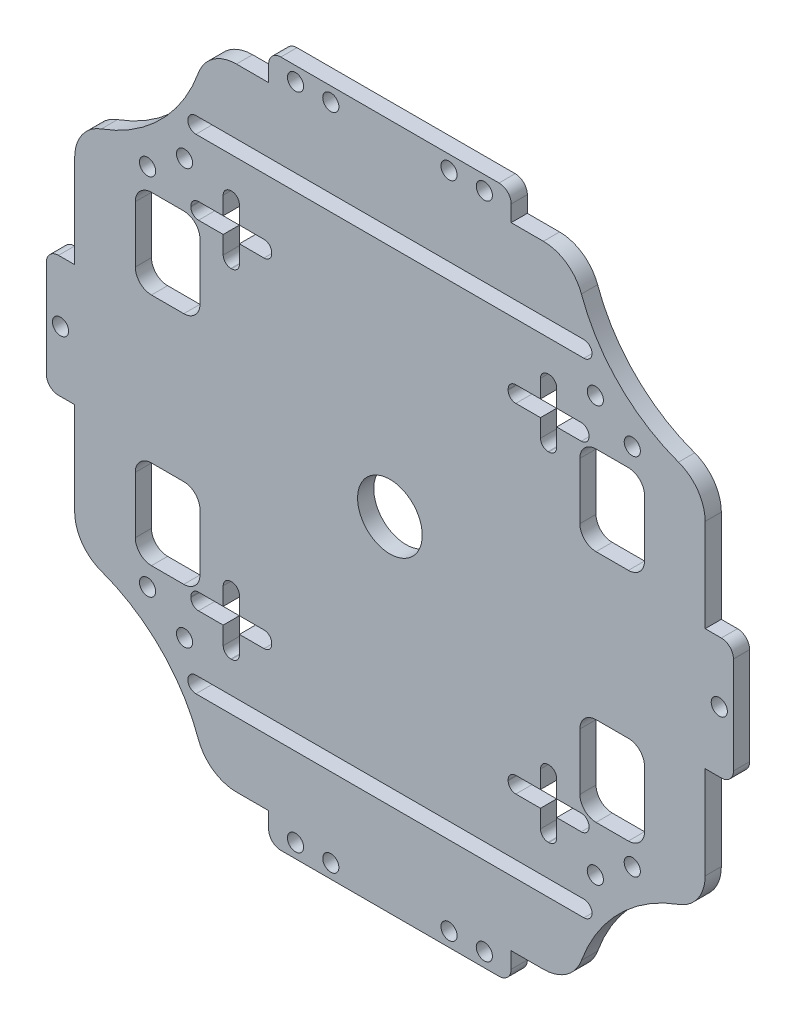
SolidWorks part; units mm, degrees
ref_plane "Front Plane" through (0, 0, 0) normal (0, 0, 1) x (1, 0, 0)
ref_plane "Top Plane" through (0, 0, 0) normal (0, 1, 0) x (1, 0, 0)
ref_plane "Right Plane" through (0, 0, 0) normal (1, 0, 0) x (0, 0, -1)
sketch "Sketch2" plane through (0, 0, 0) normal (0, 0, 1) x (1, 0, 0)
  line L0 (-37.25, 1.35) -> (-31.15, 1.35)
  line L2 (-85, -54.5) -> (-85, -30.5)
  line L4 (85, -54.5) -> (85, -30.5)
  line L7 (-27, 42.5) -> (27, 42.5)
  line L8 (30, 35.5) -> (30, 39.5)
  line L9 (30, 35.5) -> (37.9787, 35.5)
  line L10 (-30, 35.5) -> (-37.9787, 35.5)
  line L11 (-30, 35.5) -> (-30, 39.5)
  line L12 (82, -27.5) -> (78, -27.5)
  line L13 (-82, -57.5) -> (-78, -57.5)
  line L14 (78, -27.5) -> (78, -4.5213)
  line L15 (-78, -27.5) -> (-78, -4.5213)
  line L16 (-82, -27.5) -> (-78, -27.5)
  line L17 (-78, -57.5) -> (-78, -80.4787)
  line L18 (78, -57.5) -> (78, -80.4787)
  line L19 (82, -57.5) -> (78, -57.5)
  line L20 (-30, -120.5) -> (-30, -124.5)
  line L21 (-30, -120.5) -> (-37.9787, -120.5)
  line L22 (30, -120.5) -> (37.9787, -120.5)
  line L23 (30, -120.5) -> (30, -124.5)
  line L24 (-27, -127.5) -> (27, -127.5)
  line L27 (51, -2.5) -> (59, -2.5)
  line L30 (47, -6.5) -> (47, -20.5)
  line L31 (51, -24.5) -> (59, -24.5)
  line L32 (63, -6.5) -> (63, -20.5)
  line L34 (63, -78.5) -> (63, -64.5)
  line L35 (51, -82.5) -> (59, -82.5)
  line L36 (47, -78.5) -> (47, -64.5)
  line L37 (51, -60.5) -> (59, -60.5)
  line L38 (-51, -60.5) -> (-59, -60.5)
  line L39 (-47, -78.5) -> (-47, -64.5)
  line L40 (-51, -82.5) -> (-59, -82.5)
  line L41 (-63, -78.5) -> (-63, -64.5)
  line L42 (-63, -6.5) -> (-63, -20.5)
  line L43 (-51, -2.5) -> (-59, -2.5)
  line L44 (-47, -6.5) -> (-47, -20.5)
  line L45 (-51, -24.5) -> (-59, -24.5)
  line L46 (-48, -104.4522) -> (48, -104.4522)
  line L47 (-48, 19.4522) -> (48, 19.4522)
  line L49 (-48, 15.4522) -> (48, 15.4522)
  line L51 (-48, -100.4522) -> (48, -100.4522)
  line L71 (-47.35, -2.65) -> (-41.25, -2.65)
  line L72 (-49.25, -0.75) -> (-49.25, -0.55)
  line L73 (-47.35, 1.35) -> (-41.25, 1.35)
  line L74 (-29.25, -0.75) -> (-29.25, -0.55)
  line L75 (-49.25, -2.65) -> (-29.25, 1.35) construction
  line L76 (-49.25, 1.35) -> (-29.25, -2.65) construction
  line L77 (-39.35, -8.9664) -> (-39.15, -8.9664)
  line L78 (-41.25, -7.0664) -> (-41.25, -2.65)
  line L79 (-39.35, 7.6664) -> (-39.15, 7.6664)
  line L80 (-37.25, -7.0664) -> (-37.25, -2.65)
  line L81 (-41.25, -8.9664) -> (-37.25, 7.6664) construction
  line L82 (-41.25, 7.6664) -> (-37.25, -8.9664) construction
  line L83 (-37.25, 1.35) -> (-37.25, 5.7664)
  line L84 (-41.25, 1.35) -> (-41.25, 5.7664)
  line L86 (-37.25, -2.65) -> (-31.15, -2.65)
  line L87 (41.25, 7.6664) -> (37.25, -8.9664) construction
  line L88 (41.25, -8.9664) -> (37.25, 7.6664) construction
  line L89 (49.25, 1.35) -> (29.25, -2.65) construction
  line L90 (37.25, -2.65) -> (31.15, -2.65)
  line L91 (41.25, 1.35) -> (41.25, 5.7664)
  line L92 (37.25, 1.35) -> (37.25, 5.7664)
  line L93 (37.25, -7.0664) -> (37.25, -2.65)
  line L94 (39.35, 7.6664) -> (39.15, 7.6664)
  line L95 (41.25, -7.0664) -> (41.25, -2.65)
  line L96 (39.35, -8.9664) -> (39.15, -8.9664)
  line L97 (29.25, -0.75) -> (29.25, -0.55)
  line L98 (47.35, 1.35) -> (41.25, 1.35)
  line L99 (49.25, -0.75) -> (49.25, -0.55)
  line L100 (47.35, -2.65) -> (41.25, -2.65)
  line L101 (37.25, 1.35) -> (31.15, 1.35)
  line L103 (39.35, -92.6664) -> (39.15, -92.6664)
  line L104 (49.25, -84.25) -> (49.25, -84.45)
  line L105 (37.25, -86.35) -> (37.25, -90.7664)
  line L106 (37.25, -82.35) -> (31.15, -82.35)
  line L107 (29.25, -84.25) -> (29.25, -84.45)
  line L108 (37.25, -86.35) -> (31.15, -86.35)
  line L109 (41.25, -86.35) -> (41.25, -90.7664)
  line L110 (41.25, -77.9336) -> (41.25, -82.35)
  line L111 (37.25, -77.9336) -> (37.25, -82.35)
  line L112 (39.35, -76.0336) -> (39.15, -76.0336)
  line L113 (47.35, -86.35) -> (41.25, -86.35)
  line L114 (47.35, -82.35) -> (41.25, -82.35)
  line L115 (-47.35, -82.35) -> (-41.25, -82.35)
  line L116 (-47.35, -86.35) -> (-41.25, -86.35)
  line L117 (-49.25, -84.25) -> (-49.25, -84.45)
  line L118 (-39.35, -76.0336) -> (-39.15, -76.0336)
  line L119 (-37.25, -77.9336) -> (-37.25, -82.35)
  line L120 (-41.25, -77.9336) -> (-41.25, -82.35)
  line L121 (-41.25, -86.35) -> (-41.25, -90.7664)
  line L122 (-37.25, -86.35) -> (-31.15, -86.35)
  line L123 (-29.25, -84.25) -> (-29.25, -84.45)
  line L124 (-37.25, -82.35) -> (-31.15, -82.35)
  line L125 (-37.25, -86.35) -> (-37.25, -90.7664)
  line L126 (-39.35, -92.6664) -> (-39.15, -92.6664)
  arc A0 (47.383, 28.9) -> (71.4, 4.883) centre (85, 42.5) ccw
  arc A1 (-47.383, 28.9) -> (-71.4, 4.883) centre (-85, 42.5) cw
  arc A2 (47.383, 28.9) -> (37.9787, 35.5) centre (37.9787, 25.5) ccw
  arc A3 (78, -4.5213) -> (71.4, 4.883) centre (68, -4.5213) ccw
  arc A4 (-47.383, 28.9) -> (-37.9787, 35.5) centre (-37.9787, 25.5) cw
  arc A5 (-78, -4.5213) -> (-71.4, 4.883) centre (-68, -4.5213) cw
  arc A6 (27, 42.5) -> (30, 39.5) centre (27, 39.5) cw
  arc A7 (-30, 39.5) -> (-27, 42.5) centre (-27, 39.5) cw
  arc A8 (-82, -27.5) -> (-85, -30.5) centre (-82, -30.5) ccw
  arc A9 (85, -30.5) -> (82, -27.5) centre (82, -30.5) ccw
  arc A10 (85, -54.5) -> (82, -57.5) centre (82, -54.5) cw
  arc A11 (-82, -57.5) -> (-85, -54.5) centre (-82, -54.5) cw
  arc A12 (-30, -124.5) -> (-27, -127.5) centre (-27, -124.5) ccw
  arc A13 (27, -127.5) -> (30, -124.5) centre (27, -124.5) ccw
  arc A14 (-78, -80.4787) -> (-71.4, -89.883) centre (-68, -80.4787) ccw
  arc A15 (-47.383, -113.9) -> (-37.9787, -120.5) centre (-37.9787, -110.5) ccw
  arc A16 (78, -80.4787) -> (71.4, -89.883) centre (68, -80.4787) cw
  arc A17 (47.383, -113.9) -> (37.9787, -120.5) centre (37.9787, -110.5) cw
  arc A18 (-47.383, -113.9) -> (-71.4, -89.883) centre (-85, -127.5) ccw
  arc A19 (47.383, -113.9) -> (71.4, -89.883) centre (85, -127.5) cw
  circle A20 centre (81.5, -42.5) radius 2
  circle A21 centre (-81.5, -42.5) radius 2
  circle A26 centre (0, -42.5) radius 8
  arc A27 (48, 15.4522) -> (48, 19.4522) centre (48, 17.4522) ccw
  arc A28 (-48, 15.4522) -> (-48, 19.4522) centre (-48, 17.4522) cw
  arc A29 (-48, -100.4522) -> (-48, -104.4522) centre (-48, -102.4522) ccw
  arc A30 (48, -100.4522) -> (48, -104.4522) centre (48, -102.4522) cw
  circle A31 centre (50.8221, 8.8682) radius 2
  circle A32 centre (59.9673, 2.5307) radius 2
  circle A33 centre (-50.8221, 8.8682) radius 2
  circle A34 centre (-59.9673, 2.5307) radius 2
  circle A35 centre (50.8221, -93.8682) radius 2
  circle A36 centre (59.9673, -87.5307) radius 2
  circle A37 centre (-59.9673, -87.5307) radius 2
  circle A38 centre (-50.8221, -93.8682) radius 2
  arc A39 (59, -24.5) -> (63, -20.5) centre (59, -20.5) ccw
  arc A40 (51, -24.5) -> (47, -20.5) centre (51, -20.5) cw
  arc A41 (51, -2.5) -> (47, -6.5) centre (51, -6.5) ccw
  arc A42 (59, -2.5) -> (63, -6.5) centre (59, -6.5) cw
  arc A43 (47, -78.5) -> (51, -82.5) centre (51, -78.5) ccw
  arc A44 (59, -82.5) -> (63, -78.5) centre (59, -78.5) ccw
  arc A45 (63, -64.5) -> (59, -60.5) centre (59, -64.5) ccw
  arc A46 (47, -64.5) -> (51, -60.5) centre (51, -64.5) cw
  arc A47 (-63, -64.5) -> (-59, -60.5) centre (-59, -64.5) cw
  arc A48 (-63, -78.5) -> (-59, -82.5) centre (-59, -78.5) ccw
  arc A49 (-51, -82.5) -> (-47, -78.5) centre (-51, -78.5) ccw
  arc A50 (-47, -64.5) -> (-51, -60.5) centre (-51, -64.5) ccw
  arc A51 (-59, -24.5) -> (-63, -20.5) centre (-59, -20.5) cw
  arc A52 (-59, -2.5) -> (-63, -6.5) centre (-59, -6.5) ccw
  arc A53 (-47, -6.5) -> (-51, -2.5) centre (-51, -6.5) ccw
  arc A54 (-47, -20.5) -> (-51, -24.5) centre (-51, -20.5) cw
  circle A55 centre (23.3595, 39) radius 2
  circle A56 centre (14.6225, 39) radius 2
  circle A57 centre (-14.6225, 39) radius 2
  circle A58 centre (-23.3595, 39) radius 2
  circle A59 centre (-23.3595, -124) radius 2
  circle A60 centre (-14.6225, -124) radius 2
  circle A61 centre (23.3595, -124) radius 2
  circle A62 centre (14.6225, -124) radius 2
  arc A63 (-39.35, -8.9664) -> (-41.25, -7.0664) centre (-39.35, -7.0664) cw
  arc A64 (-39.15, -8.9664) -> (-37.25, -7.0664) centre (-39.15, -7.0664) ccw
  arc A65 (-37.25, 5.7664) -> (-39.15, 7.6664) centre (-39.15, 5.7664) ccw
  arc A66 (-41.25, 5.7664) -> (-39.35, 7.6664) centre (-39.35, 5.7664) cw
  arc A67 (-47.35, 1.35) -> (-49.25, -0.55) centre (-47.35, -0.55) ccw
  arc A68 (-47.35, -2.65) -> (-49.25, -0.75) centre (-47.35, -0.75) cw
  arc A69 (-31.15, -2.65) -> (-29.25, -0.75) centre (-31.15, -0.75) ccw
  arc A70 (-31.15, 1.35) -> (-29.25, -0.55) centre (-31.15, -0.55) cw
  arc A71 (31.15, 1.35) -> (29.25, -0.55) centre (31.15, -0.55) ccw
  arc A72 (31.15, -2.65) -> (29.25, -0.75) centre (31.15, -0.75) cw
  arc A73 (47.35, -2.65) -> (49.25, -0.75) centre (47.35, -0.75) ccw
  arc A74 (47.35, 1.35) -> (49.25, -0.55) centre (47.35, -0.55) cw
  arc A75 (41.25, 5.7664) -> (39.35, 7.6664) centre (39.35, 5.7664) ccw
  arc A76 (37.25, 5.7664) -> (39.15, 7.6664) centre (39.15, 5.7664) cw
  arc A77 (39.15, -8.9664) -> (37.25, -7.0664) centre (39.15, -7.0664) cw
  arc A78 (39.35, -8.9664) -> (41.25, -7.0664) centre (39.35, -7.0664) ccw
  arc A79 (31.15, -82.35) -> (29.25, -84.25) centre (31.15, -84.25) ccw
  arc A80 (31.15, -86.35) -> (29.25, -84.45) centre (31.15, -84.45) cw
  arc A81 (37.25, -90.7664) -> (39.15, -92.6664) centre (39.15, -90.7664) ccw
  arc A82 (41.25, -90.7664) -> (39.35, -92.6664) centre (39.35, -90.7664) cw
  arc A83 (39.35, -76.0336) -> (41.25, -77.9336) centre (39.35, -77.9336) cw
  arc A84 (39.15, -76.0336) -> (37.25, -77.9336) centre (39.15, -77.9336) ccw
  arc A85 (47.35, -86.35) -> (49.25, -84.45) centre (47.35, -84.45) ccw
  arc A86 (47.35, -82.35) -> (49.25, -84.25) centre (47.35, -84.25) cw
  arc A87 (-47.35, -82.35) -> (-49.25, -84.25) centre (-47.35, -84.25) ccw
  arc A88 (-47.35, -86.35) -> (-49.25, -84.45) centre (-47.35, -84.45) cw
  arc A89 (-39.15, -76.0336) -> (-37.25, -77.9336) centre (-39.15, -77.9336) cw
  arc A90 (-39.35, -76.0336) -> (-41.25, -77.9336) centre (-39.35, -77.9336) ccw
  arc A91 (-41.25, -90.7664) -> (-39.35, -92.6664) centre (-39.35, -90.7664) ccw
  arc A92 (-37.25, -90.7664) -> (-39.15, -92.6664) centre (-39.15, -90.7664) cw
  arc A93 (-31.15, -86.35) -> (-29.25, -84.45) centre (-31.15, -84.45) ccw
  arc A94 (-31.15, -82.35) -> (-29.25, -84.25) centre (-31.15, -84.25) cw
  point P0 (0, 0)
  point P17 (0, 35.5)
  point P20 (45.6173, 35.5)
  point P21 (80, -27.5)
  point P24 (-80, -27.5)
  point P28 (78, 3.1173)
  point P31 (-45.6173, 35.5)
  point P34 (-78, 3.1173)
  point P37 (30, 42.5)
  point P40 (-30, 42.5)
  point P43 (-85, -27.5)
  point P46 (85, -27.5)
  point P79 (85, -57.5)
  point P80 (-85, -57.5)
  point P81 (-30, -127.5)
  point P82 (30, -127.5)
  point P83 (-78, -88.1173)
  point P84 (-45.6173, -120.5)
  point P85 (78, -88.1173)
  point P86 (-80, -57.5)
  point P87 (45.6173, -120.5)
  point P88 (0, -120.5)
  point P137 (63, -24.5)
  point P152 (47, -24.5)
  point P155 (47, -2.5)
  point P158 (63, -2.5)
  point P161 (47, -82.5)
  point P164 (63, -82.5)
  point P167 (63, -60.5)
  point P170 (47, -60.5)
  point P173 (-63, -60.5)
  point P176 (-63, -82.5)
  point P179 (-47, -82.5)
  point P182 (-47, -60.5)
  point P185 (-63, -24.5)
  point P188 (-63, -2.5)
  point P191 (-47, -2.5)
  point P194 (-47, -24.5)
  dimension "D3" = 29.25
  dimension "D7" = 41.25
  dimension "D8" = 47
  dimension "D9" = 50.8221
  dimension "D10" = 59.9673
  dimension "D11" = 81.5
  dimension "D12" = 14.6225
  dimension "D13" = 23.3595
  dimension "D1" = 4
  dimension "D2" = 16
  dimension "D14" = 29.25
  dimension "D20" = 2.5307
  dimension "D21" = 3.1173
  dimension "D17" = 59.9673
  dimension "D22" = 4.883
  dimension "D25" = 17.4522
  dimension "D27" = 28.9
  dimension "D28" = 39
  dimension "D30" = 24.5
  dimension "D32" = 102.4522
  dimension "D33" = 124
  dimension "D4" = 30
  dimension "D5" = 37.25
  dimension "D6" = 4
  dimension "D34" = 170
  dimension "D15" = 47
  dimension "D16" = 50.8221
  dimension "D18" = 81.5
  dimension "D19" = 1.35
  dimension "D23" = 7.6664
  dimension "D24" = 8.8682
  dimension "D26" = 25.5
  dimension "D29" = 2.5
  dimension "D31" = 27.5
extrude "Boss-Extrude1" add sketch "Sketch2" against normal blind 4
